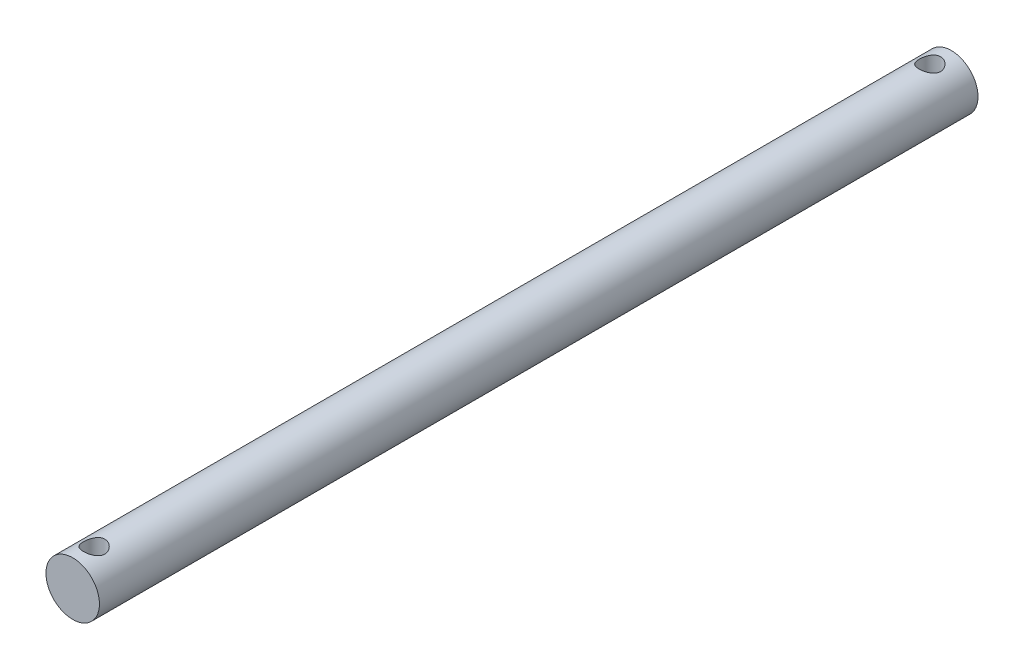
SolidWorks part; units mm, degrees
material "AISI 1020"
ref_plane "Alzado" through (0, 0, 0) normal (0, 0, 1) x (1, 0, 0)
ref_plane "Planta" through (0, 0, 0) normal (0, 1, 0) x (1, 0, 0)
ref_plane "Vista lateral" through (0, 0, 0) normal (1, 0, 0) x (0, 0, -1)
sketch "Croquis1" plane through (0, 0, 0) normal (0, 0, 1) x (1, 0, 0)
  circle A1 centre (0, 0) radius 3.9624
  dimension "D1" = 7.9248
extrude "Saliente-Extruir1" add sketch "Croquis1" along normal blind 130.175
sketch "Croquis2" plane through (0, 0, 0) normal (0, 1, 0) x (1, 0, 0)
  line L0 (0, 0) -> (0, -130.175) construction
  line L1 (3.9624, 0) -> (-3.9624, 0) construction
  circle A1 centre (0, -127) radius 1.5875
  circle A2 centre (0, -3.175) radius 1.5875
  dimension "D1" = 3.175
  dimension "D2" = 3.175
  dimension "D3" = 3.175
  dimension "D4" = 3.175
extrude "Cortar-Extruir1" cut sketch "Croquis2" against normal through all both and the other way through all
